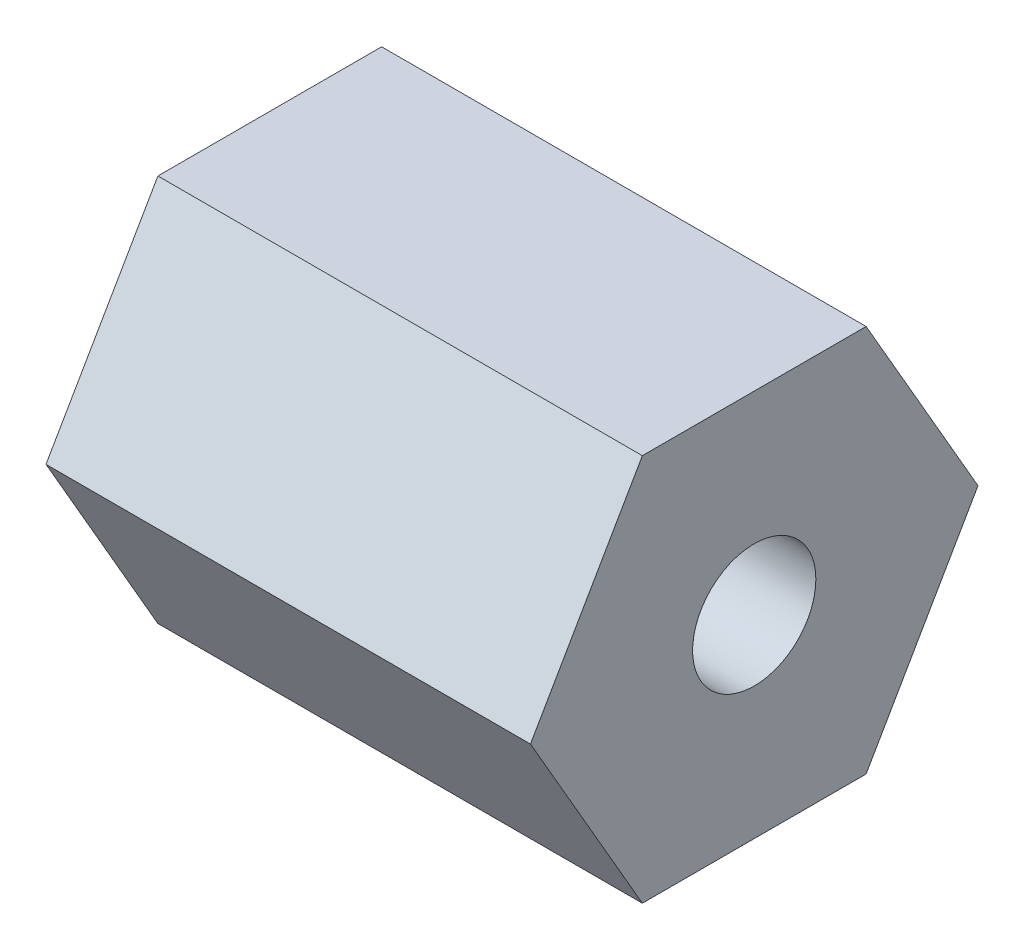
SolidWorks part; units mm, degrees
material "7075-T6 (SN)"
ref_plane "Front Plane" through (0, 0, 0) normal (0, 0, 1) x (1, 0, 0)
ref_plane "Top Plane" through (0, 0, 0) normal (0, 1, 0) x (1, 0, 0)
ref_plane "Right Plane" through (0, 0, 0) normal (1, 0, 0) x (0, 0, -1)
sketch "Sketch1" plane through (0, 0, 0) normal (1, 0, 0) x (0, 0, -1)
  line L1 (7.3323, 0) -> (3.6662, 6.35)
  line L2 (3.6662, 6.35) -> (-3.6662, 6.35)
  line L3 (-3.6662, 6.35) -> (-7.3323, 0)
  line L4 (-7.3323, 0) -> (-3.6662, -6.35)
  line L5 (-3.6662, -6.35) -> (3.6662, -6.35)
  line L6 (3.6662, -6.35) -> (7.3323, 0)
  circle A0 centre (0, 0) radius 6.35 construction
  dimension "D1" = 12.7
extrude "Boss-Extrude1" add sketch "Sketch1" along normal mid plane 15.875
hole_wizard "#10-32 Tapped Hole1" positions "3DSketch1" profile "Sketch3" tap size "#10-32" standard "ANSI Inch"
sketch3d "3DSketch1"
  line L0 (7.9375, -6.35, 3.6662) -> (7.9375, -6.35, -3.6662) construction
  line L1 (7.9375, 0, 7.3323) -> (7.9375, -6.35, 3.6662) construction
  circle A0 centre (7.9375, 0, 0) radius 6.35 construction
  point P0 (0, 0, 0)
  point P4 (0, 0, 0)
  point P6 (7.9375, 0, 0)
  point P13 (14.2875, 0, 0)
  dimension "D1" = 12.7
sketch "Sketch3" plane through (7.9375, 0, 0) normal (0, 1, 0) x (0, 0, -1)
  line L0 (0, 0) -> (0, 17.4693)
  line L1 (0, 17.4693) -> (2.0193, 16.256)
  line L2 (2.0193, 16.256) -> (2.0193, 0)
  line L5 (2.0193, 0) -> (0, 0)
  line L10 (0, 17.4693) -> (-2.0193, 16.256) construction
  line L11 (0, -6.35) -> (0, 107.95) construction
  dimension "Tap Drill Dia." = 4.0386
  dimension "Tap Drill Depth" = 16.256
  dimension "Drill Angle" = 118
cosmetic thread "Hole Thread1"
cosmetic thread "Hole Thread2"
cosmetic thread "Hole Thread3"
